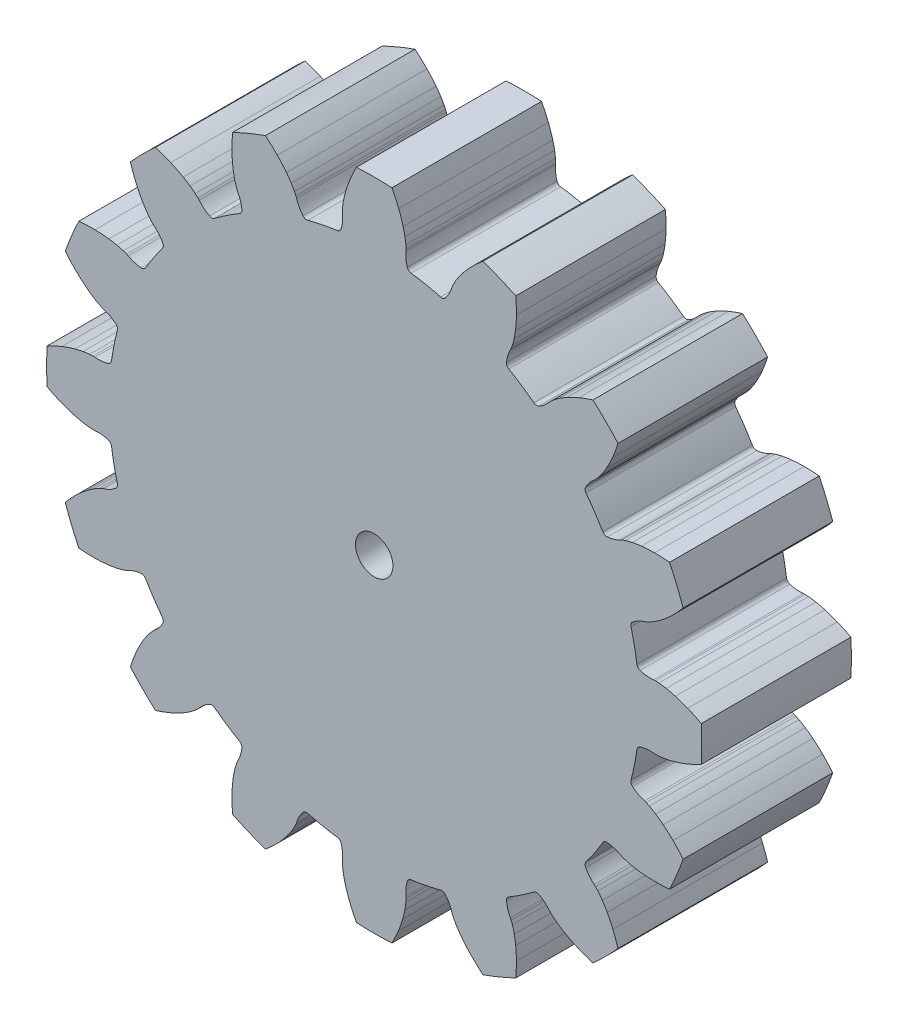
SolidWorks part; units mm, degrees
ref_plane "Front Plane" through (0, 0, 0) normal (0, 0, 1) x (1, 0, 0)
ref_plane "Top Plane" through (0, 0, 0) normal (0, 1, 0) x (1, 0, 0)
ref_plane "Right Plane" through (0, 0, 0) normal (1, 0, 0) x (0, 0, -1)
sketch "Model" plane through (0, 0, 0) normal (0, 0, 1) x (1, 0, 0)
  arc A1 (22.0867, -4.3933) -> (22.3008, -3.1302) centre (0, 0) ccw
  arc A2 (22.5768, -2.8062) -> (22.3008, -3.1302) centre (22.6938, -3.1854) ccw
  arc A3 (23.7172, -2.6934) -> (22.5768, -2.8062) centre (23.4244, -5.5546) ccw
  arc A4 (23.7172, -2.6934) -> (23.875, -2.7001) centre (23.8525, -1.3714) ccw
  arc A5 (23.875, -2.7001) -> (24.166, -2.6858) centre (23.7984, 1.8268) ccw
  arc A6 (24.166, -2.6858) -> (24.7196, -2.6123) centre (23.7188, 2.8051) ccw
  arc A7 (24.7196, -2.6123) -> (25.3944, -2.4589) centre (23.1829, 5.7052) ccw
  arc A8 (25.3944, -2.4589) -> (26.5158, -2.0827) centre (22.7771, 7.2035) ccw
  arc A9 (26.5158, -2.0827) -> (27.7636, -1.505) centre (21.4631, 10.4673) ccw
  arc A10 (27.7636, -1.505) -> (27.7636, 1.505) centre (0, 0) ccw
  arc A11 (27.7636, 1.505) -> (26.6084, 2.0452) centre (21.4412, -10.5088) ccw
  arc A12 (26.6084, 2.0452) -> (25.5573, 2.4131) centre (22.6674, -7.5296) ccw
  arc A13 (25.5573, 2.4131) -> (24.7891, 2.5997) centre (23.086, -6.0895) ccw
  arc A14 (24.7891, 2.5997) -> (24.166, 2.6858) centre (23.7109, -2.901) ccw
  arc A15 (24.166, 2.6858) -> (23.875, 2.7001) centre (23.7984, -1.8268) ccw
  arc A16 (23.875, 2.7001) -> (23.7172, 2.6934) centre (23.8525, 1.3713) ccw
  arc A17 (22.5768, 2.8062) -> (23.7172, 2.6934) centre (23.4244, 5.5546) ccw
  arc A18 (22.3008, 3.1302) -> (22.5768, 2.8062) centre (22.6938, 3.1854) ccw
  arc A19 (22.3008, 3.1302) -> (21.8011, 5.6422) centre (0, 0) ccw
  arc A20 (21.9322, 6.0472) -> (21.8011, 5.6422) centre (22.1853, 5.7416) ccw
  arc A21 (22.9426, 6.5878) -> (21.9322, 6.0472) centre (23.767, 3.8323) ccw
  arc A22 (22.9426, 6.5878) -> (23.0909, 6.642) centre (22.5616, 7.861) ccw
  arc A23 (23.0909, 6.642) -> (23.3543, 6.7666) centre (21.2878, 10.795) ccw
  arc A24 (23.3543, 6.7666) -> (23.8377, 7.0463) centre (20.8398, 11.6683) ccw
  arc A25 (23.8377, 7.0463) -> (24.4023, 7.4463) centre (19.235, 14.1426) ccw
  arc A26 (24.4023, 7.4463) -> (25.2944, 8.223) centre (18.2866, 15.3716) ccw
  arc A27 (25.2944, 8.223) -> (26.2261, 9.2342) centre (15.8237, 17.884) ccw
  arc A28 (26.2261, 9.2342) -> (25.0742, 12.0151) centre (0, 0) ccw
  arc A29 (25.0742, 12.0151) -> (23.8003, 12.0722) centre (23.8306, -1.5037) ccw
  arc A30 (23.8003, 12.0722) -> (22.6884, 12.0098) centre (23.8234, 1.718) ccw
  arc A31 (22.6884, 12.0098) -> (21.9073, 11.8881) centre (23.659, 3.2086) ccw
  arc A32 (21.9073, 11.8881) -> (21.2987, 11.7293) centre (23.0162, 6.3936) ccw
  arc A33 (21.2987, 11.7293) -> (21.0243, 11.6311) centre (22.686, 7.4196) ccw
  arc A34 (21.0243, 11.6311) -> (20.8811, 11.5646) centre (21.512, 10.3949) ccw
  arc A35 (19.7844, 11.2324) -> (20.8811, 11.5646) centre (19.5157, 14.096) ccw
  arc A36 (19.4054, 11.4261) -> (19.7844, 11.2324) centre (19.7473, 11.6274) ccw
  arc A37 (19.4054, 11.4261) -> (17.9825, 13.5557) centre (0, 0) ccw
  arc A38 (17.9485, 13.98) -> (17.9825, 13.5557) centre (18.2993, 13.7945) ccw
  arc A39 (18.6751, 14.8661) -> (17.9485, 13.98) centre (20.4913, 12.6358) ccw
  arc A40 (18.6751, 14.8661) -> (18.7914, 14.9729) centre (17.836, 15.8966) ccw
  arc A41 (18.7914, 14.9729) -> (18.9871, 15.1888) centre (15.5363, 18.1198) ccw
  arc A42 (18.9871, 15.1888) -> (19.3266, 15.6322) centre (14.7882, 18.7552) ccw
  arc A43 (19.3266, 15.6322) -> (19.6952, 16.2179) centre (12.3586, 20.427) ccw
  arc A44 (19.6952, 16.2179) -> (20.2222, 17.2768) centre (11.0122, 21.1995) ccw
  arc A45 (20.2222, 17.2768) -> (20.696, 18.5676) centre (7.7752, 22.5782) ccw
  arc A46 (20.696, 18.5676) -> (18.5676, 20.696) centre (0, 0) ccw
  arc A47 (18.5676, 20.696) -> (17.3688, 20.2612) centre (22.5921, 7.7303) ccw
  arc A48 (17.3688, 20.2612) -> (16.3654, 19.7781) centre (21.3525, 10.7041) ccw
  arc A49 (16.3654, 19.7781) -> (15.6903, 19.3668) centre (20.6302, 12.0183) ccw
  arc A50 (15.6903, 19.3668) -> (15.1888, 18.9871) centre (18.8175, 14.7148) ccw
  arc A51 (15.1888, 18.9871) -> (14.9729, 18.7914) centre (18.1198, 15.5363) ccw
  arc A52 (14.9729, 18.7914) -> (14.8661, 18.6751) centre (15.8966, 17.836) ccw
  arc A53 (13.98, 17.9485) -> (14.8661, 18.6751) centre (12.6358, 20.4913) ccw
  arc A54 (13.5557, 17.9825) -> (13.98, 17.9485) centre (13.7945, 18.2993) ccw
  arc A55 (13.5557, 17.9825) -> (11.4261, 19.4054) centre (0, 0) ccw
  arc A56 (11.2324, 19.7844) -> (11.4261, 19.4054) centre (11.6274, 19.7473) ccw
  arc A57 (11.5646, 20.8811) -> (11.2324, 19.7844) centre (14.096, 19.5157) ccw
  arc A58 (11.5646, 20.8811) -> (11.6311, 21.0243) centre (10.3949, 21.512) ccw
  arc A59 (11.6311, 21.0243) -> (11.7293, 21.2987) centre (7.4196, 22.686) ccw
  arc A60 (11.7293, 21.2987) -> (11.8733, 21.8383) centre (6.4852, 22.9867) ccw
  arc A61 (11.8733, 21.8383) -> (11.9897, 22.5204) centre (3.6008, 23.6015) ccw
  arc A62 (11.9897, 22.5204) -> (12.0713, 23.7004) centre (2.0612, 23.7999) ccw
  arc A63 (12.0713, 23.7004) -> (12.0151, 25.0742) centre (-1.4569, 23.8349) ccw
  arc A64 (12.0151, 25.0742) -> (9.2342, 26.2261) centre (0, 0) ccw
  arc A65 (9.2342, 26.2261) -> (8.293, 25.3657) centre (17.9141, 15.7875) ccw
  arc A66 (8.293, 25.3657) -> (7.5509, 24.5353) centre (15.6309, 18.0605) ccw
  arc A67 (7.5509, 24.5353) -> (7.0846, 23.897) centre (14.4606, 18.9983) ccw
  arc A68 (7.0846, 23.897) -> (6.7666, 23.3543) centre (11.754, 20.7959) ccw
  arc A69 (6.7666, 23.3543) -> (6.642, 23.0909) centre (10.795, 21.2878) ccw
  arc A70 (6.642, 23.0909) -> (6.5878, 22.9426) centre (7.861, 22.5616) ccw
  arc A71 (6.0472, 21.9322) -> (6.5878, 22.9426) centre (3.8323, 23.767) ccw
  arc A72 (5.6422, 21.8011) -> (6.0472, 21.9322) centre (5.7416, 22.1853) ccw
  arc A73 (5.6422, 21.8011) -> (3.1302, 22.3008) centre (0, 0) ccw
  arc A74 (2.8062, 22.5768) -> (3.1302, 22.3008) centre (3.1854, 22.6938) ccw
  arc A75 (2.6934, 23.7172) -> (2.8062, 22.5768) centre (5.5546, 23.4244) ccw
  arc A76 (2.6934, 23.7172) -> (2.7001, 23.875) centre (1.3714, 23.8525) ccw
  arc A77 (2.7001, 23.875) -> (2.6858, 24.166) centre (-1.8268, 23.7984) ccw
  arc A78 (2.6858, 24.166) -> (2.6123, 24.7196) centre (-2.8051, 23.7188) ccw
  arc A79 (2.6123, 24.7196) -> (2.4589, 25.3944) centre (-5.7052, 23.1829) ccw
  arc A80 (2.4589, 25.3944) -> (2.0827, 26.5158) centre (-7.2035, 22.7771) ccw
  arc A81 (2.0827, 26.5158) -> (1.505, 27.7636) centre (-10.4673, 21.4631) ccw
  arc A82 (1.505, 27.7636) -> (-1.505, 27.7636) centre (0, 0) ccw
  arc A83 (-1.505, 27.7636) -> (-2.0452, 26.6084) centre (10.5088, 21.4412) ccw
  arc A84 (-2.0452, 26.6084) -> (-2.4131, 25.5573) centre (7.5296, 22.6674) ccw
  arc A85 (-2.4131, 25.5573) -> (-2.5997, 24.7891) centre (6.0895, 23.086) ccw
  arc A86 (-2.5997, 24.7891) -> (-2.6858, 24.166) centre (2.901, 23.7109) ccw
  arc A87 (-2.6858, 24.166) -> (-2.7001, 23.875) centre (1.8268, 23.7984) ccw
  arc A88 (-2.7001, 23.875) -> (-2.6934, 23.7172) centre (-1.3713, 23.8525) ccw
  arc A89 (-2.8062, 22.5768) -> (-2.6934, 23.7172) centre (-5.5546, 23.4244) ccw
  arc A90 (-3.1302, 22.3008) -> (-2.8062, 22.5768) centre (-3.1854, 22.6938) ccw
  arc A91 (-3.1302, 22.3008) -> (-5.6422, 21.8011) centre (0, 0) ccw
  arc A92 (-6.0472, 21.9322) -> (-5.6422, 21.8011) centre (-5.7416, 22.1853) ccw
  arc A93 (-6.5878, 22.9426) -> (-6.0472, 21.9322) centre (-3.8323, 23.767) ccw
  arc A94 (-6.5878, 22.9426) -> (-6.642, 23.0909) centre (-7.861, 22.5616) ccw
  arc A95 (-6.642, 23.0909) -> (-6.7666, 23.3543) centre (-10.795, 21.2878) ccw
  arc A96 (-6.7666, 23.3543) -> (-7.0463, 23.8377) centre (-11.6683, 20.8398) ccw
  arc A97 (-7.0463, 23.8377) -> (-7.4463, 24.4023) centre (-14.1426, 19.235) ccw
  arc A98 (-7.4463, 24.4023) -> (-8.223, 25.2944) centre (-15.3716, 18.2866) ccw
  arc A99 (-8.223, 25.2944) -> (-9.2342, 26.2261) centre (-17.884, 15.8237) ccw
  arc A100 (-9.2342, 26.2261) -> (-12.0151, 25.0742) centre (0, 0) ccw
  arc A101 (-12.0151, 25.0742) -> (-12.0722, 23.8003) centre (1.5037, 23.8306) ccw
  arc A102 (-12.0722, 23.8003) -> (-12.0098, 22.6884) centre (-1.718, 23.8234) ccw
  arc A103 (-12.0098, 22.6884) -> (-11.8881, 21.9073) centre (-3.2086, 23.659) ccw
  arc A104 (-11.8881, 21.9073) -> (-11.7293, 21.2987) centre (-6.3936, 23.0162) ccw
  arc A105 (-11.7293, 21.2987) -> (-11.6311, 21.0243) centre (-7.4196, 22.686) ccw
  arc A106 (-11.6311, 21.0243) -> (-11.5646, 20.8811) centre (-10.3949, 21.512) ccw
  arc A107 (-11.2324, 19.7844) -> (-11.5646, 20.8811) centre (-14.096, 19.5157) ccw
  arc A108 (-11.4261, 19.4054) -> (-11.2324, 19.7844) centre (-11.6274, 19.7473) ccw
  arc A109 (-11.4261, 19.4054) -> (-13.5557, 17.9825) centre (0, 0) ccw
  arc A110 (-13.98, 17.9485) -> (-13.5557, 17.9825) centre (-13.7945, 18.2993) ccw
  arc A111 (-14.8661, 18.6751) -> (-13.98, 17.9485) centre (-12.6358, 20.4913) ccw
  arc A112 (-14.8661, 18.6751) -> (-14.9729, 18.7914) centre (-15.8966, 17.836) ccw
  arc A113 (-14.9729, 18.7914) -> (-15.1888, 18.9871) centre (-18.1198, 15.5363) ccw
  arc A114 (-15.1888, 18.9871) -> (-15.6322, 19.3266) centre (-18.7552, 14.7882) ccw
  arc A115 (-15.6322, 19.3266) -> (-16.2179, 19.6952) centre (-20.427, 12.3586) ccw
  arc A116 (-16.2179, 19.6952) -> (-17.2768, 20.2222) centre (-21.1995, 11.0122) ccw
  arc A117 (-17.2768, 20.2222) -> (-18.5676, 20.696) centre (-22.5782, 7.7752) ccw
  arc A118 (-18.5676, 20.696) -> (-20.696, 18.5676) centre (0, 0) ccw
  arc A119 (-20.696, 18.5676) -> (-20.2612, 17.3688) centre (-7.7303, 22.5921) ccw
  arc A120 (-20.2612, 17.3688) -> (-19.7781, 16.3654) centre (-10.7041, 21.3525) ccw
  arc A121 (-19.7781, 16.3654) -> (-19.3668, 15.6903) centre (-12.0183, 20.6302) ccw
  arc A122 (-19.3668, 15.6903) -> (-18.9871, 15.1888) centre (-14.7148, 18.8175) ccw
  arc A123 (-18.9871, 15.1888) -> (-18.7914, 14.9729) centre (-15.5363, 18.1198) ccw
  arc A124 (-18.7914, 14.9729) -> (-18.6751, 14.8661) centre (-17.836, 15.8966) ccw
  arc A125 (-17.9485, 13.98) -> (-18.6751, 14.8661) centre (-20.4913, 12.6358) ccw
  arc A126 (-17.9825, 13.5557) -> (-17.9485, 13.98) centre (-18.2993, 13.7945) ccw
  arc A127 (-17.9825, 13.5557) -> (-19.4054, 11.4261) centre (0, 0) ccw
  arc A128 (-19.7844, 11.2324) -> (-19.4054, 11.4261) centre (-19.7473, 11.6274) ccw
  arc A129 (-20.8811, 11.5646) -> (-19.7844, 11.2324) centre (-19.5157, 14.096) ccw
  arc A130 (-20.8811, 11.5646) -> (-21.0243, 11.6311) centre (-21.512, 10.3949) ccw
  arc A131 (-21.0243, 11.6311) -> (-21.2987, 11.7293) centre (-22.686, 7.4196) ccw
  arc A132 (-21.2987, 11.7293) -> (-21.8383, 11.8733) centre (-22.9867, 6.4852) ccw
  arc A133 (-21.8383, 11.8733) -> (-22.5204, 11.9897) centre (-23.6015, 3.6008) ccw
  arc A134 (-22.5204, 11.9897) -> (-23.7004, 12.0713) centre (-23.7999, 2.0612) ccw
  arc A135 (-23.7004, 12.0713) -> (-25.0742, 12.0151) centre (-23.8349, -1.4569) ccw
  arc A136 (-25.0742, 12.0151) -> (-26.2261, 9.2342) centre (0, 0) ccw
  arc A137 (-26.2261, 9.2342) -> (-25.3657, 8.293) centre (-15.7875, 17.9141) ccw
  arc A138 (-25.3657, 8.293) -> (-24.5353, 7.5509) centre (-18.0605, 15.6309) ccw
  arc A139 (-24.5353, 7.5509) -> (-23.897, 7.0846) centre (-18.9983, 14.4606) ccw
  arc A140 (-23.897, 7.0846) -> (-23.3543, 6.7666) centre (-20.7959, 11.754) ccw
  arc A141 (-23.3543, 6.7666) -> (-23.0909, 6.642) centre (-21.2878, 10.795) ccw
  arc A142 (-23.0909, 6.642) -> (-22.9426, 6.5878) centre (-22.5616, 7.861) ccw
  arc A143 (-21.9322, 6.0472) -> (-22.9426, 6.5878) centre (-23.767, 3.8323) ccw
  arc A144 (-21.8011, 5.6422) -> (-21.9322, 6.0472) centre (-22.1853, 5.7416) ccw
  arc A145 (-21.8011, 5.6422) -> (-22.3008, 3.1302) centre (0, 0) ccw
  arc A146 (-22.5768, 2.8062) -> (-22.3008, 3.1302) centre (-22.6938, 3.1854) ccw
  arc A147 (-23.7172, 2.6934) -> (-22.5768, 2.8062) centre (-23.4244, 5.5546) ccw
  arc A148 (-23.7172, 2.6934) -> (-23.875, 2.7001) centre (-23.8525, 1.3714) ccw
  arc A149 (-23.875, 2.7001) -> (-24.166, 2.6858) centre (-23.7984, -1.8268) ccw
  arc A150 (-24.166, 2.6858) -> (-24.7196, 2.6123) centre (-23.7188, -2.8051) ccw
  arc A151 (-24.7196, 2.6123) -> (-25.3944, 2.4589) centre (-23.1829, -5.7052) ccw
  arc A152 (-25.3944, 2.4589) -> (-26.5158, 2.0827) centre (-22.7771, -7.2035) ccw
  arc A153 (-26.5158, 2.0827) -> (-27.7636, 1.505) centre (-21.4631, -10.4673) ccw
  arc A154 (-27.7636, 1.505) -> (-27.7636, -1.505) centre (0, 0) ccw
  arc A155 (-27.7636, -1.505) -> (-26.6084, -2.0452) centre (-21.4412, 10.5088) ccw
  arc A156 (-26.6084, -2.0452) -> (-25.5573, -2.4131) centre (-22.6674, 7.5296) ccw
  arc A157 (-25.5573, -2.4131) -> (-24.7891, -2.5997) centre (-23.086, 6.0895) ccw
  arc A158 (-24.7891, -2.5997) -> (-24.166, -2.6858) centre (-23.7109, 2.901) ccw
  arc A159 (-24.166, -2.6858) -> (-23.875, -2.7001) centre (-23.7984, 1.8268) ccw
  arc A160 (-23.875, -2.7001) -> (-23.7172, -2.6934) centre (-23.8525, -1.3713) ccw
  arc A161 (-22.5768, -2.8062) -> (-23.7172, -2.6934) centre (-23.4244, -5.5546) ccw
  arc A162 (-22.3008, -3.1302) -> (-22.5768, -2.8062) centre (-22.6938, -3.1854) ccw
  arc A163 (-22.3008, -3.1302) -> (-21.8011, -5.6422) centre (0, 0) ccw
  arc A164 (-21.9322, -6.0472) -> (-21.8011, -5.6422) centre (-22.1853, -5.7416) ccw
  arc A165 (-22.9426, -6.5878) -> (-21.9322, -6.0472) centre (-23.767, -3.8323) ccw
  arc A166 (-22.9426, -6.5878) -> (-23.0909, -6.642) centre (-22.5616, -7.861) ccw
  arc A167 (-23.0909, -6.642) -> (-23.3543, -6.7666) centre (-21.2878, -10.795) ccw
  arc A168 (-23.3543, -6.7666) -> (-23.8377, -7.0463) centre (-20.8398, -11.6683) ccw
  arc A169 (-23.8377, -7.0463) -> (-24.4023, -7.4463) centre (-19.235, -14.1426) ccw
  arc A170 (-24.4023, -7.4463) -> (-25.2944, -8.223) centre (-18.2866, -15.3716) ccw
  arc A171 (-25.2944, -8.223) -> (-26.2261, -9.2342) centre (-15.8237, -17.884) ccw
  arc A172 (-26.2261, -9.2342) -> (-25.0742, -12.0151) centre (0, 0) ccw
  arc A173 (-25.0742, -12.0151) -> (-23.8003, -12.0722) centre (-23.8306, 1.5037) ccw
  arc A174 (-23.8003, -12.0722) -> (-22.6884, -12.0098) centre (-23.8234, -1.718) ccw
  arc A175 (-22.6884, -12.0098) -> (-21.9073, -11.8881) centre (-23.659, -3.2086) ccw
  arc A176 (-21.9073, -11.8881) -> (-21.2987, -11.7293) centre (-23.0162, -6.3936) ccw
  arc A177 (-21.2987, -11.7293) -> (-21.0243, -11.6311) centre (-22.686, -7.4196) ccw
  arc A178 (-21.0243, -11.6311) -> (-20.8811, -11.5646) centre (-21.512, -10.3949) ccw
  arc A179 (-19.7844, -11.2324) -> (-20.8811, -11.5646) centre (-19.5157, -14.096) ccw
  arc A180 (-19.4054, -11.4261) -> (-19.7844, -11.2324) centre (-19.7473, -11.6274) ccw
  arc A181 (-19.4054, -11.4261) -> (-17.9825, -13.5557) centre (0, 0) ccw
  arc A182 (-17.9485, -13.98) -> (-17.9825, -13.5557) centre (-18.2993, -13.7945) ccw
  arc A183 (-18.6751, -14.8661) -> (-17.9485, -13.98) centre (-20.4913, -12.6358) ccw
  arc A184 (-18.6751, -14.8661) -> (-18.7914, -14.9729) centre (-17.836, -15.8966) ccw
  arc A185 (-18.7914, -14.9729) -> (-18.9871, -15.1888) centre (-15.5363, -18.1198) ccw
  arc A186 (-18.9871, -15.1888) -> (-19.3266, -15.6322) centre (-14.7882, -18.7552) ccw
  arc A187 (-19.3266, -15.6322) -> (-19.6952, -16.2179) centre (-12.3586, -20.427) ccw
  arc A188 (-19.6952, -16.2179) -> (-20.2222, -17.2768) centre (-11.0122, -21.1995) ccw
  arc A189 (-20.2222, -17.2768) -> (-20.696, -18.5676) centre (-7.7752, -22.5782) ccw
  arc A190 (-20.696, -18.5676) -> (-18.5676, -20.696) centre (0, 0) ccw
  arc A191 (-18.5676, -20.696) -> (-17.3688, -20.2612) centre (-22.5921, -7.7303) ccw
  arc A192 (-17.3688, -20.2612) -> (-16.3654, -19.7781) centre (-21.3525, -10.7041) ccw
  arc A193 (-16.3654, -19.7781) -> (-15.6903, -19.3668) centre (-20.6302, -12.0183) ccw
  arc A194 (-15.6903, -19.3668) -> (-15.1888, -18.9871) centre (-18.8175, -14.7148) ccw
  arc A195 (-15.1888, -18.9871) -> (-14.9729, -18.7914) centre (-18.1198, -15.5363) ccw
  arc A196 (-14.9729, -18.7914) -> (-14.8661, -18.6751) centre (-15.8966, -17.836) ccw
  arc A197 (-13.98, -17.9485) -> (-14.8661, -18.6751) centre (-12.6358, -20.4913) ccw
  arc A198 (-13.5557, -17.9825) -> (-13.98, -17.9485) centre (-13.7945, -18.2993) ccw
  arc A199 (-13.5557, -17.9825) -> (-11.4261, -19.4054) centre (0, 0) ccw
  arc A200 (-11.2324, -19.7844) -> (-11.4261, -19.4054) centre (-11.6274, -19.7473) ccw
  arc A201 (-11.5646, -20.8811) -> (-11.2324, -19.7844) centre (-14.096, -19.5157) ccw
  arc A202 (-11.5646, -20.8811) -> (-11.6311, -21.0243) centre (-10.3949, -21.512) ccw
  arc A203 (-11.6311, -21.0243) -> (-11.7293, -21.2987) centre (-7.4196, -22.686) ccw
  arc A204 (-11.7293, -21.2987) -> (-11.8733, -21.8383) centre (-6.4852, -22.9867) ccw
  arc A205 (-11.8733, -21.8383) -> (-11.9897, -22.5204) centre (-3.6008, -23.6015) ccw
  arc A206 (-11.9897, -22.5204) -> (-12.0713, -23.7004) centre (-2.0612, -23.7999) ccw
  arc A207 (-12.0713, -23.7004) -> (-12.0151, -25.0742) centre (1.4569, -23.8349) ccw
  arc A208 (-12.0151, -25.0742) -> (-9.2342, -26.2261) centre (0, 0) ccw
  arc A209 (-9.2342, -26.2261) -> (-8.293, -25.3657) centre (-17.9141, -15.7875) ccw
  arc A210 (-8.293, -25.3657) -> (-7.5509, -24.5353) centre (-15.6309, -18.0605) ccw
  arc A211 (-7.5509, -24.5353) -> (-7.0846, -23.897) centre (-14.4606, -18.9983) ccw
  arc A212 (-7.0846, -23.897) -> (-6.7666, -23.3543) centre (-11.754, -20.7959) ccw
  arc A213 (-6.7666, -23.3543) -> (-6.642, -23.0909) centre (-10.795, -21.2878) ccw
  arc A214 (-6.642, -23.0909) -> (-6.5878, -22.9426) centre (-7.861, -22.5616) ccw
  arc A215 (-6.0472, -21.9322) -> (-6.5878, -22.9426) centre (-3.8323, -23.767) ccw
  arc A216 (-5.6422, -21.8011) -> (-6.0472, -21.9322) centre (-5.7416, -22.1853) ccw
  arc A217 (-5.6422, -21.8011) -> (-3.1302, -22.3008) centre (0, 0) ccw
  arc A218 (-2.8062, -22.5768) -> (-3.1302, -22.3008) centre (-3.1854, -22.6938) ccw
  arc A219 (-2.6934, -23.7172) -> (-2.8062, -22.5768) centre (-5.5546, -23.4244) ccw
  arc A220 (-2.6934, -23.7172) -> (-2.7001, -23.875) centre (-1.3714, -23.8525) ccw
  arc A221 (-2.7001, -23.875) -> (-2.6858, -24.166) centre (1.8268, -23.7984) ccw
  arc A222 (-2.6858, -24.166) -> (-2.6123, -24.7196) centre (2.8051, -23.7188) ccw
  arc A223 (-2.6123, -24.7196) -> (-2.4589, -25.3944) centre (5.7052, -23.1829) ccw
  arc A224 (-2.4589, -25.3944) -> (-2.0827, -26.5158) centre (7.2035, -22.7771) ccw
  arc A225 (-2.0827, -26.5158) -> (-1.505, -27.7636) centre (10.4673, -21.4631) ccw
  arc A226 (-1.505, -27.7636) -> (1.505, -27.7636) centre (0, 0) ccw
  arc A227 (1.505, -27.7636) -> (2.0452, -26.6084) centre (-10.5088, -21.4412) ccw
  arc A228 (2.0452, -26.6084) -> (2.4131, -25.5573) centre (-7.5296, -22.6674) ccw
  arc A229 (2.4131, -25.5573) -> (2.5997, -24.7891) centre (-6.0895, -23.086) ccw
  arc A230 (2.5997, -24.7891) -> (2.6858, -24.166) centre (-2.901, -23.7109) ccw
  arc A231 (2.6858, -24.166) -> (2.7001, -23.875) centre (-1.8268, -23.7984) ccw
  arc A232 (2.7001, -23.875) -> (2.6934, -23.7172) centre (1.3713, -23.8525) ccw
  arc A233 (2.8062, -22.5768) -> (2.6934, -23.7172) centre (5.5546, -23.4244) ccw
  arc A234 (3.1302, -22.3008) -> (2.8062, -22.5768) centre (3.1854, -22.6938) ccw
  arc A235 (3.1302, -22.3008) -> (5.6422, -21.8011) centre (0, 0) ccw
  arc A236 (6.0472, -21.9322) -> (5.6422, -21.8011) centre (5.7416, -22.1853) ccw
  arc A237 (6.5878, -22.9426) -> (6.0472, -21.9322) centre (3.8323, -23.767) ccw
  arc A238 (6.5878, -22.9426) -> (6.642, -23.0909) centre (7.861, -22.5616) ccw
  arc A239 (6.642, -23.0909) -> (6.7666, -23.3543) centre (10.795, -21.2878) ccw
  arc A240 (6.7666, -23.3543) -> (7.0463, -23.8377) centre (11.6683, -20.8398) ccw
  arc A241 (7.0463, -23.8377) -> (7.4463, -24.4023) centre (14.1426, -19.235) ccw
  arc A242 (7.4463, -24.4023) -> (8.223, -25.2944) centre (15.3716, -18.2866) ccw
  arc A243 (8.223, -25.2944) -> (9.2342, -26.2261) centre (17.884, -15.8237) ccw
  arc A244 (9.2342, -26.2261) -> (12.0151, -25.0742) centre (0, 0) ccw
  arc A245 (12.0151, -25.0742) -> (12.0722, -23.8003) centre (-1.5037, -23.8306) ccw
  arc A246 (12.0722, -23.8003) -> (12.0098, -22.6884) centre (1.718, -23.8234) ccw
  arc A247 (12.0098, -22.6884) -> (11.8881, -21.9073) centre (3.2086, -23.659) ccw
  arc A248 (11.8881, -21.9073) -> (11.7293, -21.2987) centre (6.3936, -23.0162) ccw
  arc A249 (11.7293, -21.2987) -> (11.6311, -21.0243) centre (7.4196, -22.686) ccw
  arc A250 (11.6311, -21.0243) -> (11.5646, -20.8811) centre (10.3949, -21.512) ccw
  arc A251 (11.2324, -19.7844) -> (11.5646, -20.8811) centre (14.096, -19.5157) ccw
  arc A252 (11.4261, -19.4054) -> (11.2324, -19.7844) centre (11.6274, -19.7473) ccw
  arc A253 (11.4261, -19.4054) -> (13.5557, -17.9825) centre (0, 0) ccw
  arc A254 (13.98, -17.9485) -> (13.5557, -17.9825) centre (13.7945, -18.2993) ccw
  arc A255 (14.8661, -18.6751) -> (13.98, -17.9485) centre (12.6358, -20.4913) ccw
  arc A256 (14.8661, -18.6751) -> (14.9729, -18.7914) centre (15.8966, -17.836) ccw
  arc A257 (14.9729, -18.7914) -> (15.1888, -18.9871) centre (18.1198, -15.5363) ccw
  arc A258 (15.1888, -18.9871) -> (15.6322, -19.3266) centre (18.7552, -14.7882) ccw
  arc A259 (15.6322, -19.3266) -> (16.2179, -19.6952) centre (20.427, -12.3586) ccw
  arc A260 (16.2179, -19.6952) -> (17.2768, -20.2222) centre (21.1995, -11.0122) ccw
  arc A261 (17.2768, -20.2222) -> (18.5676, -20.696) centre (22.5782, -7.7752) ccw
  arc A262 (18.5676, -20.696) -> (20.696, -18.5676) centre (0, 0) ccw
  arc A263 (20.696, -18.5676) -> (20.2612, -17.3688) centre (7.7303, -22.5921) ccw
  arc A264 (20.2612, -17.3688) -> (19.7781, -16.3654) centre (10.7041, -21.3525) ccw
  arc A265 (19.7781, -16.3654) -> (19.3668, -15.6903) centre (12.0183, -20.6302) ccw
  arc A266 (19.3668, -15.6903) -> (18.9871, -15.1888) centre (14.7148, -18.8175) ccw
  arc A267 (18.9871, -15.1888) -> (18.7914, -14.9729) centre (15.5363, -18.1198) ccw
  arc A268 (18.7914, -14.9729) -> (18.6751, -14.8661) centre (17.836, -15.8966) ccw
  arc A269 (17.9485, -13.98) -> (18.6751, -14.8661) centre (20.4913, -12.6358) ccw
  arc A270 (17.9825, -13.5557) -> (17.9485, -13.98) centre (18.2993, -13.7945) ccw
  arc A271 (17.9825, -13.5557) -> (19.4054, -11.4261) centre (0, 0) ccw
  arc A272 (19.7844, -11.2324) -> (19.4054, -11.4261) centre (19.7473, -11.6274) ccw
  arc A273 (20.8811, -11.5646) -> (19.7844, -11.2324) centre (19.5157, -14.096) ccw
  arc A274 (20.8811, -11.5646) -> (21.0243, -11.6311) centre (21.512, -10.3949) ccw
  arc A275 (21.0243, -11.6311) -> (21.2987, -11.7293) centre (22.686, -7.4196) ccw
  arc A276 (21.2987, -11.7293) -> (21.8383, -11.8733) centre (22.9867, -6.4852) ccw
  arc A277 (21.8383, -11.8733) -> (22.5204, -11.9897) centre (23.6015, -3.6008) ccw
  arc A278 (22.5204, -11.9897) -> (23.7004, -12.0713) centre (23.7999, -2.0612) ccw
  arc A279 (23.7004, -12.0713) -> (25.0742, -12.0151) centre (23.8349, 1.4569) ccw
  arc A280 (25.0742, -12.0151) -> (26.2261, -9.2342) centre (0, 0) ccw
  arc A281 (26.2261, -9.2342) -> (25.3657, -8.293) centre (15.7875, -17.9141) ccw
  arc A282 (25.3657, -8.293) -> (24.5353, -7.5509) centre (18.0605, -15.6309) ccw
  arc A283 (24.5353, -7.5509) -> (23.897, -7.0846) centre (18.9983, -14.4606) ccw
  arc A284 (23.897, -7.0846) -> (23.3543, -6.7666) centre (20.7959, -11.754) ccw
  arc A285 (23.3543, -6.7666) -> (23.0909, -6.642) centre (21.2878, -10.795) ccw
  arc A286 (23.0909, -6.642) -> (22.9426, -6.5878) centre (22.5616, -7.861) ccw
  arc A287 (21.9322, -6.0472) -> (22.9426, -6.5878) centre (23.767, -3.8323) ccw
  arc A288 (21.8011, -5.6422) -> (21.9322, -6.0472) centre (22.1853, -5.7416) ccw
  arc A289 (21.8011, -5.6422) -> (22.0867, -4.3933) centre (0, 0) ccw
extrude "Boss-Extrude1" add sketch "Model" along normal blind 12.7
sketch "Sketch2" plane through (0, 0, 12.7) normal (0, 0, 1) x (1, 0, 0)
  circle A0 centre (0, 0) radius 1.5875
  dimension "D1" = 3.175
extrude "Cut-Extrude1" cut sketch "Sketch2" against normal through all
